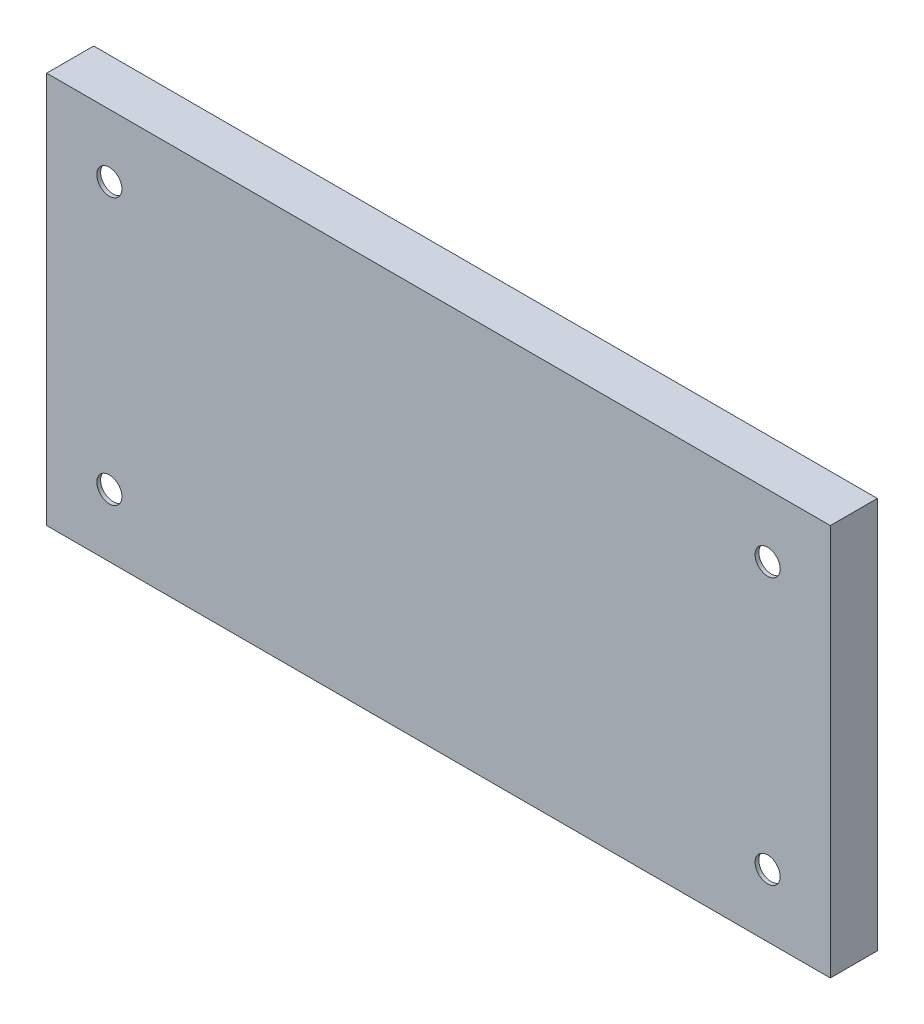
SolidWorks part; units mm, degrees
ref_plane "前视基准面" through (0, 0, 0) normal (0, 0, 1) x (1, 0, 0)
ref_plane "上视基准面" through (0, 0, 0) normal (0, 1, 0) x (1, 0, 0)
ref_plane "右视基准面" through (0, 0, 0) normal (1, 0, 0) x (0, 0, -1)
sketch "草图1" plane through (0, 0, 0) normal (0, 0, 1) x (1, 0, 0)
  line L0 (-125, -62.5) -> (-125, 62.5)
  line L1 (-125, -62.5) -> (125, -62.5)
  line L2 (-125, 62.5) -> (125, 62.5)
  line L3 (125, -62.5) -> (125, 62.5)
  line L4 (-125, -62.5) -> (125, 62.5) construction
  line L5 (-125, 62.5) -> (125, -62.5) construction
  point P1 (0, 0)
  dimension "D1" = 250
  dimension "D2" = 125
extrude "凸台-拉伸1" add sketch "草图1" along normal blind 15
shell "抽壳1" thickness 1.2
sketch "草图2" plane through (0, 0, 15) normal (0, 0, 1) x (1, 0, 0)
  line L8 (0, 0) -> (64.7146, 0) construction
  line L9 (0, 0) -> (0, 31.2342) construction
  circle A0 centre (-105, 42.5) radius 4
  circle A1 centre (105, 42.5) radius 4
  circle A2 centre (105, -42.5) radius 4
  circle A3 centre (-105, -42.5) radius 4
  dimension "D3" = 8
extrude "切除-拉伸1" cut sketch "草图2" against normal blind 15
